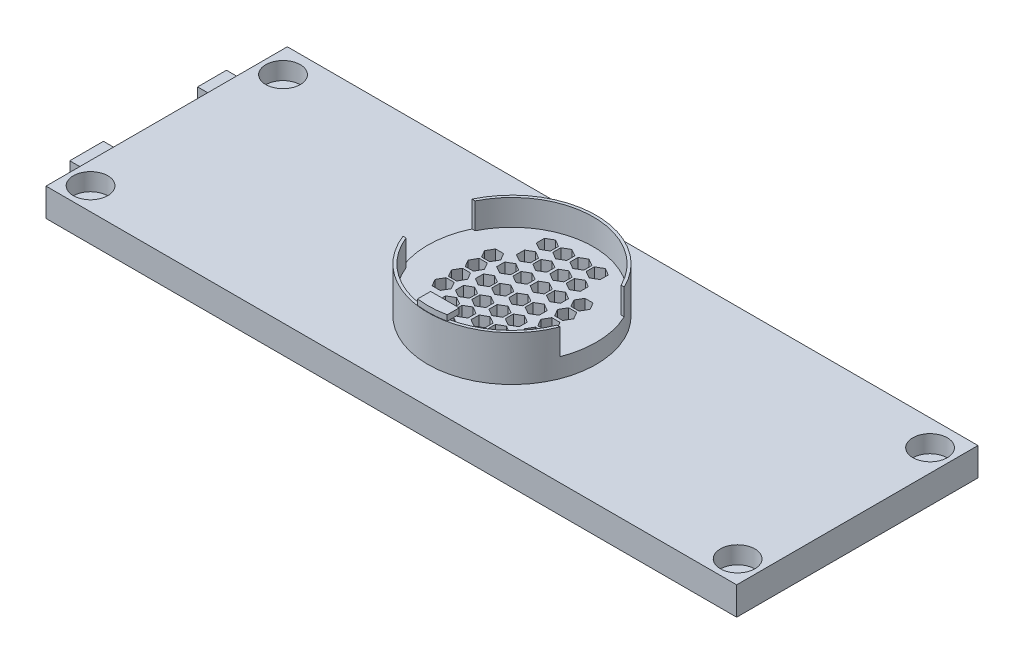
SolidWorks part; units mm, degrees
ref_plane "Front Plane" through (0, 0, 0) normal (0, 0, 1) x (1, 0, 0)
ref_plane "Top Plane" through (0, 0, 0) normal (0, 1, 0) x (1, 0, 0)
ref_plane "Right Plane" through (0, 0, 0) normal (1, 0, 0) x (0, 0, -1)
sketch "Sketch1" plane through (0, 0, 0) normal (0, 1, 0) x (1, 0, 0)
  line L1 (61.4917, -21.4874) -> (-61.4917, -21.4874)
  line L2 (61.4917, -21.4874) -> (61.4917, 21.4874)
  line L3 (61.4917, 21.4874) -> (-61.4917, 21.4874)
  line L4 (-61.4917, -21.4874) -> (-61.4917, 21.4874)
  line L5 (61.4917, -21.4874) -> (-61.4917, 21.4874) construction
  line L6 (61.4917, 21.4874) -> (-61.4917, -21.4874) construction
  point P0 (0, 0)
extrude "Boss-Extrude1" add sketch "Sketch1" along normal blind 5
sketch "Sketch2" plane through (0, 5, 0) normal (0, 1, 0) x (1, 0, 0)
  line L0 (-61.4917, 21.4874) -> (-53.5, 21.4874) construction
  line L1 (61.4917, 21.4874) -> (-61.4917, 21.4874) construction
sketch "Sketch3" plane through (0, 5, 0) normal (0, 1, 0) x (1, 0, 0)
  line L0 (-57.5802, 22.2791) -> (-57.5802, -22.461) construction
  line L1 (57.5677, 22.3499) -> (57.5677, -22.3902) construction
  line L2 (-57.4959, 21.4874) -> (-57.4959, -21.4874) construction
  line L3 (-61.4917, 21.4874) -> (-53.5, 21.4874) construction
  line L4 (-61.4917, -21.4874) -> (61.4917, -21.4874) construction
  circle A0 centre (-57.5802, 16.8075) radius 3.075
  circle A1 centre (-57.5802, -17.461) radius 3.075
  circle A2 centre (57.5677, 16.8783) radius 3.075
  circle A3 centre (57.5677, -17.3902) radius 3.075
extrude "Cut-Extrude1" cut sketch "Sketch3" against normal blind 3.1
sketch "Sketch5" plane through (-61.4917, 0, 0) normal (-1, 0, 0) x (0, 0, 1)
  line L0 (-22.3979, 2.4922) -> (22.3422, 2.4922) construction
  line L1 (-13.7478, 1.7003) -> (-13.7478, 3.7003)
  line L2 (-13.7478, 1.7003) -> (-8.6053, 1.7003)
  line L3 (-8.6053, 1.7003) -> (-8.6053, 3.7003)
  line L4 (-13.7478, 3.7003) -> (-8.6053, 3.7003)
  line L5 (-8.6053, 1.7003) -> (8.1572, 1.7003) construction
  line L9 (14.1572, 3.6937) -> (8.1572, 3.6937)
  line L10 (8.1572, 1.6901) -> (8.1572, 3.6937)
  line L11 (14.1572, 1.6901) -> (8.1572, 1.6901)
  line L12 (14.1572, 1.6901) -> (14.1572, 3.6937)
  line L13 (-21.4874, 2.5) -> (21.4874, 2.5) construction
  line L14 (-21.4874, 5) -> (-21.4874, 0) construction
  line L15 (21.4874, 5) -> (21.4874, 0) construction
  point P2 (-11.2129, 2.4922)
  point P11 (11.1572, 2.4922)
  dimension "D1" = 2
extrude "Boss-Extrude2" add sketch "Sketch5" along normal blind 3.1
sketch "Sketch6" plane through (0, 5, 0) normal (0, 1, 0) x (1, 0, 0)
  circle A0 centre (0, 0) radius 15
extrude "Boss-Extrude3" add sketch "Sketch6" along normal blind 8
sketch "Sketch8" plane through (0, 13, 0) normal (0, 1, 0) x (1, 0, 0)
  circle A0 centre (0, 0) radius 14.5
extrude "Cut-Extrude2" cut sketch "Sketch8" against normal blind 4.6
sketch "Sketch9" plane through (0, 8.4, 0) normal (0, 1, 0) x (1, 0, 0)
  line L0 (-18.3405, -5.4356) -> (20.9474, -5.4356)
  line L1 (20.9474, -5.4356) -> (20.9474, 6.4298)
  line L2 (20.9474, 6.4298) -> (-18.3405, 6.4298)
  line L3 (-18.3405, 6.4298) -> (-18.3405, -5.4356)
extrude "Cut-Extrude5" cut sketch "Sketch9" along normal blind 9.6
ref_plane "Plane1" through (13.9805, 13, 5.4356) normal (0.3624, 0, -0.932) x (-0.932, 0, -0.3624)
sketch "Sketch11" plane through (0, 13, 0) normal (0, 1, 0) x (1, 0, 0)
  line L0 (-2.0086, -12.4834) -> (-2.0086, -14.8138)
  line L1 (0, -12.4834) -> (-2.0086, -12.4834)
  line L3 (-2.0086, -12.4834) -> (3.0728, -12.4834)
  line L5 (3.0728, -12.4834) -> (3.0728, -14.6075)
  arc A3 (-2.0086, -14.8138) -> (3.0728, -14.6075) centre (-0.1027, 0.9217) ccw
extrude "Boss-Extrude5" add sketch "Sketch11" along normal blind 1 contours L3 L5 A3 L0
sketch "Sketch12" plane through (0, 0, 0) normal (0, -1, 0) x (1, 0, 0)
  line L0 (0, 14.5) -> (0, -14.5) construction
  line L1 (-15, 0) -> (15, 0) construction
  line L17 (-1.3814, -4.9711) -> (-0.1328, -4.2503)
  line L36 (-0.1328, -4.2503) -> (-0.1328, -2.8085)
  line L37 (-0.1328, -2.8085) -> (-1.3814, -2.0876)
  line L38 (-1.3814, -2.0876) -> (-2.63, -2.8085)
  line L39 (-2.63, -2.8085) -> (-2.63, -4.2503)
  line L40 (-2.63, -4.2503) -> (-1.3814, -4.9711)
  line L46 (-4.2896, -4.9711) -> (-3.041, -4.2503)
  line L47 (-3.041, -4.2503) -> (-3.041, -2.8085)
  line L48 (-3.041, -2.8085) -> (-4.2896, -2.0876)
  line L49 (-4.2896, -2.0876) -> (-5.5382, -2.8085)
  line L50 (-5.5382, -2.8085) -> (-5.5382, -4.2503)
  line L51 (-5.5382, -4.2503) -> (-4.2896, -4.9711)
  line L52 (4.5464, -5.001) -> (5.795, -4.2801)
  line L53 (5.795, -4.2801) -> (5.795, -2.8384)
  line L54 (5.795, -2.8384) -> (4.5464, -2.1175)
  line L55 (4.5464, -2.1175) -> (3.2978, -2.8384)
  line L56 (3.2978, -2.8384) -> (3.2978, -4.2801)
  line L57 (3.2978, -4.2801) -> (4.5464, -5.001)
  line L58 (1.6382, -5.001) -> (2.8868, -4.2801)
  line L59 (2.8868, -4.2801) -> (2.8868, -2.8384)
  line L60 (2.8868, -2.8384) -> (1.6382, -2.1175)
  line L61 (1.6382, -2.1175) -> (0.3896, -2.8384)
  line L62 (0.3896, -2.8384) -> (0.3896, -4.2801)
  line L63 (0.3896, -4.2801) -> (1.6382, -5.001)
  line L64 (-1.4428, -1.2342) -> (-0.1942, -0.5133)
  line L65 (-0.1942, -0.5133) -> (-0.1942, 0.9284)
  line L66 (-0.1942, 0.9284) -> (-1.4428, 1.6493)
  line L67 (-1.4428, 1.6493) -> (-2.6914, 0.9284)
  line L68 (-2.6914, 0.9284) -> (-2.6914, -0.5133)
  line L69 (-2.6914, -0.5133) -> (-1.4428, -1.2342)
  line L70 (-4.351, -1.2342) -> (-3.1025, -0.5133)
  line L71 (-3.1025, -0.5133) -> (-3.1025, 0.9284)
  line L72 (-3.1025, 0.9284) -> (-4.351, 1.6493)
  line L73 (-4.351, 1.6493) -> (-5.5996, 0.9284)
  line L74 (-5.5996, 0.9284) -> (-5.5996, -0.5133)
  line L75 (-5.5996, -0.5133) -> (-4.351, -1.2342)
  line L76 (4.4849, -1.2641) -> (5.7335, -0.5432)
  line L77 (5.7335, -0.5432) -> (5.7335, 0.8985)
  line L78 (5.7335, 0.8985) -> (4.4849, 1.6194)
  line L79 (4.4849, 1.6194) -> (3.2363, 0.8985)
  line L80 (3.2363, 0.8985) -> (3.2363, -0.5432)
  line L81 (3.2363, -0.5432) -> (4.4849, -1.2641)
  line L82 (1.5767, -1.2641) -> (2.8253, -0.5432)
  line L83 (2.8253, -0.5432) -> (2.8253, 0.8985)
  line L84 (2.8253, 0.8985) -> (1.5767, 1.6194)
  line L85 (1.5767, 1.6194) -> (0.3281, 0.8985)
  line L86 (0.3281, 0.8985) -> (0.3281, -0.5432)
  line L87 (0.3281, -0.5432) -> (1.5767, -1.2641)
  line L88 (-1.4428, 2.3085) -> (-0.1942, 3.0293)
  line L89 (-0.1942, 3.0293) -> (-0.1942, 4.4711)
  line L90 (-0.1942, 4.4711) -> (-1.4428, 5.192)
  line L91 (-1.4428, 5.192) -> (-2.6914, 4.4711)
  line L92 (-2.6914, 4.4711) -> (-2.6914, 3.0293)
  line L93 (-2.6914, 3.0293) -> (-1.4428, 2.3085)
  line L94 (-4.351, 2.3085) -> (-3.1025, 3.0293)
  line L95 (-3.1025, 3.0293) -> (-3.1025, 4.4711)
  line L96 (-3.1025, 4.4711) -> (-4.351, 5.192)
  line L97 (-4.351, 5.192) -> (-5.5996, 4.4711)
  line L98 (-5.5996, 4.4711) -> (-5.5996, 3.0293)
  line L99 (-5.5996, 3.0293) -> (-4.351, 2.3085)
  line L100 (4.4849, 2.2786) -> (5.7335, 2.9995)
  line L101 (5.7335, 2.9995) -> (5.7335, 4.4412)
  line L102 (5.7335, 4.4412) -> (4.4849, 5.1621)
  line L103 (4.4849, 5.1621) -> (3.2363, 4.4412)
  line L104 (3.2363, 4.4412) -> (3.2363, 2.9995)
  line L105 (3.2363, 2.9995) -> (4.4849, 2.2786)
  line L106 (1.5767, 2.2786) -> (2.8253, 2.9995)
  line L107 (2.8253, 2.9995) -> (2.8253, 4.4412)
  line L108 (2.8253, 4.4412) -> (1.5767, 5.1621)
  line L109 (1.5767, 5.1621) -> (0.3281, 4.4412)
  line L110 (0.3281, 4.4412) -> (0.3281, 2.9995)
  line L111 (0.3281, 2.9995) -> (1.5767, 2.2786)
  line L112 (-1.4248, 5.5165) -> (-0.1763, 6.2374)
  line L113 (-0.1763, 6.2374) -> (-0.1763, 7.6792)
  line L114 (-0.1763, 7.6792) -> (-1.4248, 8.4)
  line L115 (-1.4248, 8.4) -> (-2.6734, 7.6792)
  line L116 (-2.6734, 7.6792) -> (-2.6734, 6.2374)
  line L117 (-2.6734, 6.2374) -> (-1.4248, 5.5165)
  line L118 (-4.3331, 5.5165) -> (-3.0845, 6.2374)
  line L119 (-3.0845, 6.2374) -> (-3.0845, 7.6792)
  line L120 (-3.0845, 7.6792) -> (-4.3331, 8.4)
  line L121 (-4.3331, 8.4) -> (-5.5816, 7.6792)
  line L122 (-5.5816, 7.6792) -> (-5.5816, 6.2374)
  line L123 (-5.5816, 6.2374) -> (-4.3331, 5.5165)
  line L124 (4.5029, 5.4867) -> (5.7515, 6.2075)
  line L125 (5.7515, 6.2075) -> (5.7515, 7.6493)
  line L126 (5.7515, 7.6493) -> (4.5029, 8.3702)
  line L127 (4.5029, 8.3702) -> (3.2543, 7.6493)
  line L128 (3.2543, 7.6493) -> (3.2543, 6.2075)
  line L129 (3.2543, 6.2075) -> (4.5029, 5.4867)
  line L130 (1.5947, 5.4867) -> (2.8433, 6.2075)
  line L131 (2.8433, 6.2075) -> (2.8433, 7.6493)
  line L132 (2.8433, 7.6493) -> (1.5947, 8.3702)
  line L133 (1.5947, 8.3702) -> (0.3461, 7.6493)
  line L134 (0.3461, 7.6493) -> (0.3461, 6.2075)
  line L135 (0.3461, 6.2075) -> (1.5947, 5.4867)
  line L136 (-1.4064, 8.9229) -> (-0.1579, 9.6438)
  line L137 (-0.1579, 9.6438) -> (-0.1579, 11.0856)
  line L138 (-0.1579, 11.0856) -> (-1.4064, 11.8064)
  line L139 (-1.4064, 11.8064) -> (-2.655, 11.0856)
  line L140 (-2.655, 11.0856) -> (-2.655, 9.6438)
  line L141 (-2.655, 9.6438) -> (-1.4064, 8.9229)
  line L142 (-4.3147, 8.9229) -> (-3.0661, 9.6438)
  line L143 (-3.0661, 9.6438) -> (-3.0661, 11.0856)
  line L144 (-3.0661, 11.0856) -> (-4.3147, 11.8064)
  line L145 (-4.3147, 11.8064) -> (-5.5633, 11.0856)
  line L146 (-5.5633, 11.0856) -> (-5.5633, 9.6438)
  line L147 (-5.5633, 9.6438) -> (-4.3147, 8.9229)
  line L148 (4.5213, 8.8931) -> (5.7699, 9.6139)
  line L149 (5.7699, 9.6139) -> (5.7699, 11.0557)
  line L150 (5.7699, 11.0557) -> (4.5213, 11.7766)
  line L151 (4.5213, 11.7766) -> (3.2727, 11.0557)
  line L152 (3.2727, 11.0557) -> (3.2727, 9.6139)
  line L153 (3.2727, 9.6139) -> (4.5213, 8.8931)
  line L154 (1.6131, 8.8931) -> (2.8617, 9.6139)
  line L155 (2.8617, 9.6139) -> (2.8617, 11.0557)
  line L156 (2.8617, 11.0557) -> (1.6131, 11.7766)
  line L157 (1.6131, 11.7766) -> (0.3645, 11.0557)
  line L158 (0.3645, 11.0557) -> (0.3645, 9.6139)
  line L159 (0.3645, 9.6139) -> (1.6131, 8.8931)
  line L160 (-1.4667, -8.5789) -> (-0.2181, -7.858)
  line L161 (-0.2181, -7.858) -> (-0.2181, -6.4163)
  line L162 (-0.2181, -6.4163) -> (-1.4667, -5.6954)
  line L163 (-1.4667, -5.6954) -> (-2.7153, -6.4163)
  line L164 (-2.7153, -6.4163) -> (-2.7153, -7.858)
  line L165 (-2.7153, -7.858) -> (-1.4667, -8.5789)
  line L166 (-4.3749, -8.5789) -> (-3.1263, -7.858)
  line L167 (-3.1263, -7.858) -> (-3.1263, -6.4163)
  line L168 (-3.1263, -6.4163) -> (-4.3749, -5.6954)
  line L169 (-4.3749, -5.6954) -> (-5.6235, -6.4163)
  line L170 (-5.6235, -6.4163) -> (-5.6235, -7.858)
  line L171 (-5.6235, -7.858) -> (-4.3749, -8.5789)
  line L172 (4.461, -8.6088) -> (5.7096, -7.8879)
  line L173 (5.7096, -7.8879) -> (5.7096, -6.4461)
  line L174 (5.7096, -6.4461) -> (4.461, -5.7253)
  line L175 (4.461, -5.7253) -> (3.2124, -6.4461)
  line L176 (3.2124, -6.4461) -> (3.2124, -7.8879)
  line L177 (3.2124, -7.8879) -> (4.461, -8.6088)
  line L178 (1.5528, -8.6088) -> (2.8014, -7.8879)
  line L179 (2.8014, -7.8879) -> (2.8014, -6.4461)
  line L180 (2.8014, -6.4461) -> (1.5528, -5.7253)
  line L181 (1.5528, -5.7253) -> (0.3042, -6.4461)
  line L182 (0.3042, -6.4461) -> (0.3042, -7.8879)
  line L183 (0.3042, -7.8879) -> (1.5528, -8.6088)
  line L184 (-1.5025, -12.1629) -> (-0.2539, -11.442)
  line L185 (-0.2539, -11.442) -> (-0.2539, -10.0003)
  line L186 (-0.2539, -10.0003) -> (-1.5025, -9.2794)
  line L187 (-1.5025, -9.2794) -> (-2.7511, -10.0003)
  line L188 (-2.7511, -10.0003) -> (-2.7511, -11.442)
  line L189 (-2.7511, -11.442) -> (-1.5025, -12.1629)
  line L190 (-4.4107, -12.1629) -> (-3.1621, -11.442)
  line L191 (-3.1621, -11.442) -> (-3.1621, -10.0003)
  line L192 (-3.1621, -10.0003) -> (-4.4107, -9.2794)
  line L193 (-4.4107, -9.2794) -> (-5.6593, -10.0003)
  line L194 (-5.6593, -10.0003) -> (-5.6593, -11.442)
  line L195 (-5.6593, -11.442) -> (-4.4107, -12.1629)
  line L196 (4.4253, -12.1928) -> (5.6739, -11.4719)
  line L197 (5.6739, -11.4719) -> (5.6739, -10.0301)
  line L198 (5.6739, -10.0301) -> (4.4253, -9.3093)
  line L199 (4.4253, -9.3093) -> (3.1767, -10.0301)
  line L200 (3.1767, -10.0301) -> (3.1767, -11.4719)
  line L201 (3.1767, -11.4719) -> (4.4253, -12.1928)
  line L202 (1.5171, -12.1928) -> (2.7657, -11.4719)
  line L203 (2.7657, -11.4719) -> (2.7657, -10.0301)
  line L204 (2.7657, -10.0301) -> (1.5171, -9.3093)
  line L205 (1.5171, -9.3093) -> (0.2685, -10.0301)
  line L206 (0.2685, -10.0301) -> (0.2685, -11.4719)
  line L207 (0.2685, -11.4719) -> (1.5171, -12.1928)
  line L208 (-6.2102, -1.2905) -> (-6.9311, -0.0419)
  line L209 (-6.9311, -0.0419) -> (-8.3728, -0.0419)
  line L210 (-8.3728, -0.0419) -> (-9.0937, -1.2905)
  line L211 (-9.0937, -1.2905) -> (-8.3728, -2.539)
  line L212 (-8.3728, -2.539) -> (-6.9311, -2.539)
  line L213 (-6.9311, -2.539) -> (-6.2102, -1.2905)
  line L214 (-6.2102, -4.1987) -> (-6.9311, -2.9501)
  line L215 (-6.9311, -2.9501) -> (-8.3728, -2.9501)
  line L216 (-8.3728, -2.9501) -> (-9.0937, -4.1987)
  line L217 (-9.0937, -4.1987) -> (-8.3728, -5.4473)
  line L218 (-8.3728, -5.4473) -> (-6.9311, -5.4473)
  line L219 (-6.9311, -5.4473) -> (-6.2102, -4.1987)
  line L220 (-6.1803, 4.6373) -> (-6.9012, 5.8859)
  line L221 (-6.9012, 5.8859) -> (-8.3429, 5.8859)
  line L222 (-8.3429, 5.8859) -> (-9.0638, 4.6373)
  line L223 (-9.0638, 4.6373) -> (-8.3429, 3.3887)
  line L224 (-8.3429, 3.3887) -> (-6.9012, 3.3887)
  line L225 (-6.9012, 3.3887) -> (-6.1803, 4.6373)
  line L226 (-6.1803, 1.7291) -> (-6.9012, 2.9777)
  line L227 (-6.9012, 2.9777) -> (-8.3429, 2.9777)
  line L228 (-8.3429, 2.9777) -> (-9.0638, 1.7291)
  line L229 (-9.0638, 1.7291) -> (-8.3429, 0.4805)
  line L230 (-8.3429, 0.4805) -> (-6.9012, 0.4805)
  line L231 (-6.9012, 0.4805) -> (-6.1803, 1.7291)
  line L232 (9.3641, -1.6319) -> (8.6432, -0.3833)
  line L233 (8.6432, -0.3833) -> (7.2014, -0.3833)
  line L234 (7.2014, -0.3833) -> (6.4806, -1.6319)
  line L235 (6.4806, -1.6319) -> (7.2014, -2.8804)
  line L236 (7.2014, -2.8804) -> (8.6432, -2.8804)
  line L237 (8.6432, -2.8804) -> (9.3641, -1.6319)
  line L238 (9.3641, -4.5401) -> (8.6432, -3.2915)
  line L239 (8.6432, -3.2915) -> (7.2014, -3.2915)
  line L240 (7.2014, -3.2915) -> (6.4806, -4.5401)
  line L241 (6.4806, -4.5401) -> (7.2014, -5.7887)
  line L242 (7.2014, -5.7887) -> (8.6432, -5.7887)
  line L243 (8.6432, -5.7887) -> (9.3641, -4.5401)
  line L244 (9.3939, 4.2959) -> (8.6731, 5.5445)
  line L245 (8.6731, 5.5445) -> (7.2313, 5.5445)
  line L246 (7.2313, 5.5445) -> (6.5104, 4.2959)
  line L247 (6.5104, 4.2959) -> (7.2313, 3.0473)
  line L248 (7.2313, 3.0473) -> (8.6731, 3.0473)
  line L249 (8.6731, 3.0473) -> (9.3939, 4.2959)
  line L250 (9.3939, 1.3877) -> (8.6731, 2.6363)
  line L251 (8.6731, 2.6363) -> (7.2313, 2.6363)
  line L252 (7.2313, 2.6363) -> (6.5104, 1.3877)
  line L253 (6.5104, 1.3877) -> (7.2313, 0.1391)
  line L254 (7.2313, 0.1391) -> (8.6731, 0.1391)
  line L255 (8.6731, 0.1391) -> (9.3939, 1.3877)
  circle A0 centre (-1.4248, 6.9583) radius 1.2486 construction
  circle A12 centre (-1.3814, -3.5294) radius 1.2486 construction
  circle A14 centre (-4.2896, -3.5294) radius 1.2486 construction
  circle A15 centre (4.5464, -3.5593) radius 1.2486 construction
  circle A16 centre (1.6382, -3.5593) radius 1.2486 construction
  circle A17 centre (-1.4428, 0.2075) radius 1.2486 construction
  circle A18 centre (-4.351, 0.2075) radius 1.2486 construction
  circle A19 centre (4.4849, 0.1777) radius 1.2486 construction
  circle A20 centre (1.5767, 0.1777) radius 1.2486 construction
  circle A21 centre (-1.4428, 3.7502) radius 1.2486 construction
  circle A22 centre (-4.351, 3.7502) radius 1.2486 construction
  circle A23 centre (4.4849, 3.7203) radius 1.2486 construction
  circle A24 centre (1.5767, 3.7203) radius 1.2486 construction
  circle A25 centre (-4.3331, 6.9583) radius 1.2486 construction
  circle A26 centre (4.5029, 6.9284) radius 1.2486 construction
  circle A27 centre (1.5947, 6.9284) radius 1.2486 construction
  circle A28 centre (-1.4064, 10.3647) radius 1.2486 construction
  circle A29 centre (-4.3147, 10.3647) radius 1.2486 construction
  circle A30 centre (4.5213, 10.3348) radius 1.2486 construction
  circle A31 centre (1.6131, 10.3348) radius 1.2486 construction
  circle A32 centre (-1.4667, -7.1372) radius 1.2486 construction
  circle A33 centre (-4.3749, -7.1372) radius 1.2486 construction
  circle A34 centre (4.461, -7.167) radius 1.2486 construction
  circle A35 centre (1.5528, -7.167) radius 1.2486 construction
  circle A36 centre (-1.5025, -10.7211) radius 1.2486 construction
  circle A37 centre (-4.4107, -10.7211) radius 1.2486 construction
  circle A38 centre (4.4253, -10.751) radius 1.2486 construction
  circle A39 centre (1.5171, -10.751) radius 1.2486 construction
  circle A40 centre (-7.6519, -1.2905) radius 1.2486 construction
  circle A41 centre (-7.6519, -4.1987) radius 1.2486 construction
  circle A42 centre (-7.6221, 4.6373) radius 1.2486 construction
  circle A43 centre (-7.6221, 1.7291) radius 1.2486 construction
  circle A44 centre (7.9223, -1.6319) radius 1.2486 construction
  circle A45 centre (7.9223, -4.5401) radius 1.2486 construction
  circle A46 centre (7.9522, 4.2959) radius 1.2486 construction
  circle A47 centre (7.9522, 1.3877) radius 1.2486 construction
extrude "Cut-Extrude6" cut sketch "Sketch12" against normal blind 10
